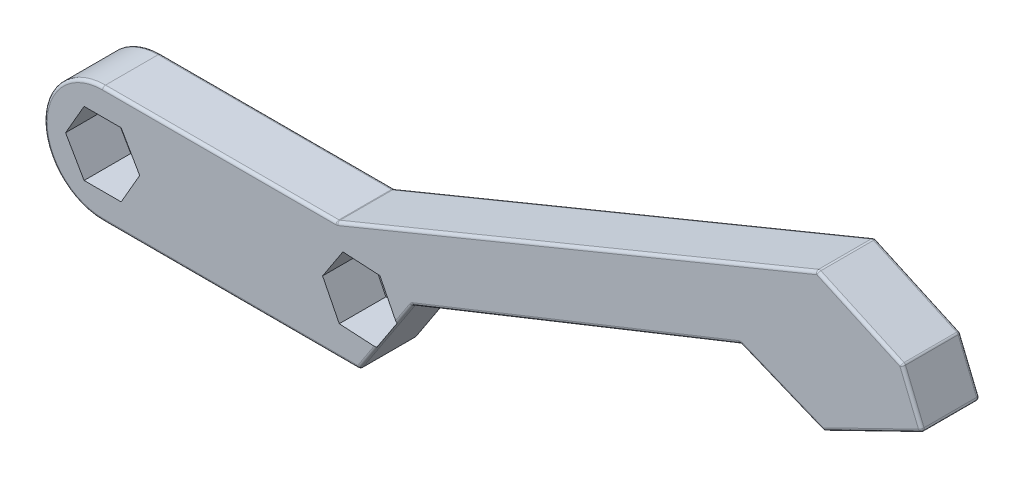
SolidWorks part; units mm, degrees
ref_plane "Front Plane" through (0, 0, 0) normal (0, 0, 1) x (1, 0, 0)
ref_plane "Top Plane" through (0, 0, 0) normal (0, 1, 0) x (1, 0, 0)
ref_plane "Right Plane" through (0, 0, 0) normal (1, 0, 0) x (0, 0, -1)
sketch "Sketch1" plane through (0, 0, 0) normal (0, 0, 1) x (1, 0, 0)
  line L0 (-25.2186, -6.4645) -> (-3.2186, -6.4645) construction
  line L1 (-25.2186, -1.4645) -> (-3.2186, -1.4645)
  line L2 (-25.2186, -11.4645) -> (-3.2186, -11.4645)
  line L3 (-5.1686, -1.4645) -> (-1.2272, -11.0508) construction
  line L4 (-5.1686, -1.4645) -> (41.0753, 17.5487) construction
  line L5 (-1.2272, -11.0508) -> (45.0167, 7.9624) construction
  line L6 (41.0753, 17.5487) -> (45.0167, 7.9624) construction
  line L7 (-5.1686, -1.4645) -> (35.9884, 15.4572)
  line L8 (35.9884, 15.4572) -> (43.3055, 12.1243)
  line L9 (43.3055, 12.1243) -> (45.0167, 7.9624)
  line L10 (35.7679, 4.1597) -> (29.4506, 6.7428)
  line L11 (29.4506, 6.7428) -> (1.3656, -4.4682)
  line L12 (35.7679, 4.1597) -> (45.0167, 7.9624) construction
  line L16 (35.7679, 4.1597) -> (36.5723, 3.8437)
  line L23 (36.5723, 3.8437) -> (45.0167, 7.9624)
  line L24 (1.3656, -4.4682) -> (-3.2186, -11.4645)
  arc A0 (-25.2186, -1.4645) -> (-25.2186, -11.4645) centre (-25.2186, -6.4645) ccw
  arc A1 (-3.2186, -11.4645) -> (-3.2186, -1.4645) centre (-3.2186, -6.4645) ccw
  circle A2 centre (-25.2186, -6.4645) radius 1.65
  circle A3 centre (-3.1979, -6.2576) radius 1.65
  point P2 (-14.2186, -6.4645)
  dimension "D11" = 3.3
  dimension "D1" = 10
  dimension "D2" = 22
  dimension "D3" = 157.65
  dimension "D4" = 1.95
  dimension "D5" = 5.5
  dimension "D6" = 4.5
  dimension "D7" = 10
  dimension "D8" = 136
  dimension "D9" = 50
  dimension "D10" = 30.24
extrude "Boss-Extrude1" add sketch "Sketch1" along normal blind 5
fillet "Fillet2" radius 0.25 31 edges at (-14.2186, -11.4645, 0) (-14.2186, -11.4645, 5) (-30.2186, -6.4645, 0) (-30.2186, -6.4645, 5) (32.6093, 5.4513, 0) (32.6093, 5.4513, 5) (-15.1936, -1.4645, 0) (-15.1936, -1.4645, 5) (45.0167, 7.9624, 2.5) (44.1611, 10.0434, 0) (44.1611, 10.0434, 5) (43.3055, 12.1243, 2.5) (39.647, 13.7908, 0) (39.647, 13.7908, 5) (15.4081, 1.1373, 0) (15.4081, 1.1373, 5) (29.4506, 6.7428, 2.5) (-3.2186, -11.4645, 2.5) (-0.9265, -7.9663, 0) (-0.9265, -7.9663, 5) (1.3656, -4.4682, 2.5) (35.9884, 15.4572, 2.5) (15.4099, 6.9964, 0) (15.4099, 6.9964, 5) (-5.1686, -1.4645, 2.5) (36.1701, 4.0017, 0) (36.1701, 4.0017, 5) (36.5723, 3.8437, 2.5) (40.7945, 5.903, 0) (40.7945, 5.903, 5) (35.7679, 4.1597, 2.5)
sketch "Sketch2" plane through (0, 0, 5) normal (0, 0, 1) x (1, 0, 0)
  line L1 (-23.6309, -9.2145) -> (-22.0432, -6.4645)
  line L2 (-22.0432, -6.4645) -> (-23.6309, -3.7145)
  line L3 (-23.6309, -3.7145) -> (-26.8063, -3.7145)
  line L4 (-26.8063, -3.7145) -> (-28.3941, -6.4645)
  line L5 (-28.3941, -6.4645) -> (-26.8063, -9.2145)
  line L6 (-26.8063, -9.2145) -> (-23.6309, -9.2145)
  line L8 (-25.2186, -11.2145) -> (-3.3537, -11.2145) construction
  line L9 (-3.3537, -11.2145) -> (1.1132, -4.3971) construction
  line L10 (-0.0276, -6.4368) -> (-1.4576, -3.6016)
  line L11 (-1.4576, -3.6016) -> (-4.628, -3.4224)
  line L12 (-4.628, -3.4224) -> (-6.3683, -6.0785)
  line L13 (-6.3683, -6.0785) -> (-4.9383, -8.9137)
  line L14 (-4.9383, -8.9137) -> (-1.7679, -9.0928)
  line L15 (-1.7679, -9.0928) -> (-0.0276, -6.4368)
  circle A0 centre (-25.2186, -6.4645) radius 2.75 construction
  circle A1 centre (-3.1979, -6.2576) radius 2.75 construction
  dimension "D1" = 5.5
  dimension "D2" = 5.5
extrude "Cut-Extrude1" cut sketch "Sketch2" against normal blind 4
